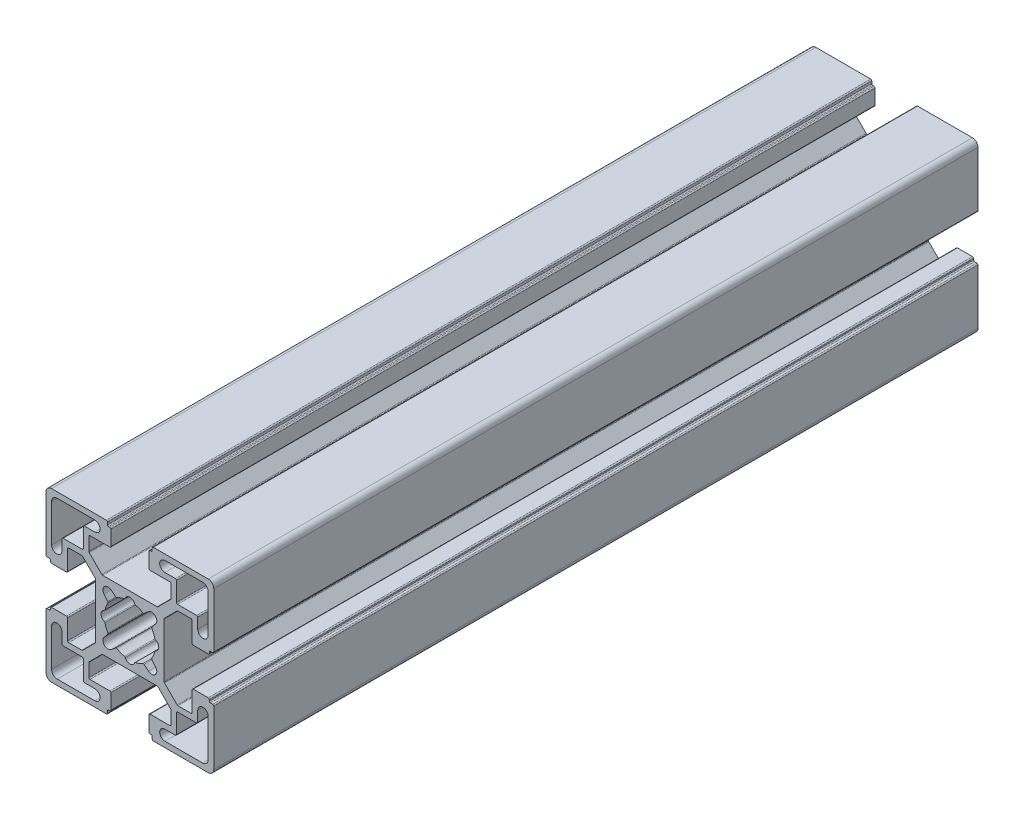
SolidWorks part; units mm, degrees
material "6063-T5"
ref_plane "Plane1" through (0, 0, 0) normal (0, 0, 1) x (1, 0, 0)
ref_plane "Plane2" through (0, 0, 0) normal (0, 1, 0) x (1, 0, 0)
ref_plane "Plane3" through (0, 0, 0) normal (1, 0, 0) x (0, 0, -1)
sketch "Sketch1" plane through (0, 0, 0) normal (0, 0, 1) x (1, 0, 0)
  line L0 (-3.8182, 5.9298) -> (-5.0112, 6.9114)
  line L1 (-6.9114, 5.0112) -> (-5.9298, 3.8182)
  line L2 (-5.9298, -3.8182) -> (-6.9114, -5.0112)
  line L3 (-5.0112, -6.9114) -> (-3.8182, -5.9298)
  line L4 (3.8182, -5.9298) -> (5.0112, -6.9114)
  line L5 (6.9114, -5.0112) -> (5.9298, -3.8182)
  line L6 (5.9298, 3.8182) -> (6.9114, 5.0112)
  line L7 (5.0112, 6.9114) -> (3.8182, 5.9298)
  line L8 (-19.5, -21) -> (-9.4, -21)
  line L9 (-9.4, -18.2) -> (-12.2, -18.2)
  line L10 (-12.5, -17.9) -> (-12.5, -12.8)
  line L11 (-12.8, -12.5) -> (-17.9, -12.5)
  line L12 (-18.2, -12.2) -> (-18.2, -9.4)
  line L13 (-21, -9.4) -> (-21, -19.5)
  line L14 (17.9, -12.5) -> (12.8, -12.5)
  line L15 (12.5, -12.8) -> (12.5, -17.9)
  line L16 (12.2, -18.2) -> (9.4, -18.2)
  line L17 (9.4, -21) -> (19.5, -21)
  line L18 (21, -19.5) -> (21, -9.4)
  line L19 (18.2, -9.4) -> (18.2, -12.2)
  line L20 (19.5, 21) -> (9.4, 21)
  line L21 (9.4, 18.2) -> (12.2, 18.2)
  line L22 (12.5, 17.9) -> (12.5, 12.8)
  line L23 (12.8, 12.5) -> (17.9, 12.5)
  line L24 (18.2, 12.2) -> (18.2, 9.4)
  line L25 (21, 9.4) -> (21, 19.5)
  line L26 (-18.2, 9.4) -> (-18.2, 12.2)
  line L27 (-17.9, 12.5) -> (-12.8, 12.5)
  line L28 (-12.5, 12.8) -> (-12.5, 17.9)
  line L29 (-12.2, 18.2) -> (-9.4, 18.2)
  line L30 (-9.4, 21) -> (-19.5, 21)
  line L31 (-21, 19.5) -> (-21, 9.4)
  line L32 (22.5, 6.3) -> (22.5, 21)
  line L33 (21.6, 6) -> (22.2, 6)
  line L34 (21.3, 5.4) -> (21.3, 5.7)
  line L36 (16.7, 10.7) -> (16.7, 5.4)
  line L37 (12.892, 11) -> (16.4, 11)
  line L38 (9.2879, 7.5201) -> (12.6799, 10.9121)
  line L39 (9.2, -7.308) -> (9.2, 7.308)
  line L40 (12.6799, -10.9121) -> (9.2879, -7.5201)
  line L41 (16.4, -11) -> (12.892, -11)
  line L42 (16.7, -5.4) -> (16.7, -10.7)
  line L44 (21.3, -5.7) -> (21.3, -5.4)
  line L45 (22.2, -6) -> (21.6, -6)
  line L46 (22.5, -21) -> (22.5, -6.3)
  line L47 (6.3, -22.5) -> (21, -22.5)
  line L48 (6, -21.6) -> (6, -22.2)
  line L49 (5.4, -21.3) -> (5.7, -21.3)
  line L51 (10.7, -16.7) -> (5.4, -16.7)
  line L52 (11, -12.892) -> (11, -16.4)
  line L53 (7.5201, -9.2879) -> (10.9121, -12.6799)
  line L54 (-7.4322, -9.2) -> (7.308, -9.2)
  line L55 (-10.9121, -12.6799) -> (-7.4322, -9.2)
  line L56 (-11, -16.4) -> (-11, -12.892)
  line L57 (-5.4, -16.7) -> (-10.7, -16.7)
  line L59 (-5.7, -21.3) -> (-5.4, -21.3)
  line L60 (-6, -22.2) -> (-6, -21.6)
  line L61 (-21, -22.5) -> (-6.3, -22.5)
  line L62 (-22.5, -6.3) -> (-22.5, -21)
  line L63 (-21.6, -6) -> (-22.2, -6)
  line L64 (-21.3, -5.4) -> (-21.3, -5.7)
  line L66 (-16.7, -10.7) -> (-16.7, -5.4)
  line L67 (-12.892, -11) -> (-16.4, -11)
  line L68 (-9.2879, -7.5201) -> (-12.6799, -10.9121)
  line L69 (-9.2, 7.308) -> (-9.2, -7.308)
  line L70 (-12.6799, 10.9121) -> (-9.2879, 7.5201)
  line L71 (-16.4, 11) -> (-12.892, 11)
  line L72 (-16.7, 5.4) -> (-16.7, 10.7)
  line L74 (-21.3, 5.7) -> (-21.3, 5.4)
  line L75 (-22.2, 6) -> (-21.6, 6)
  line L76 (-22.5, 21) -> (-22.5, 6.3)
  line L77 (-6.3, 22.5) -> (-21, 22.5)
  line L78 (-6, 21.6) -> (-6, 22.2)
  line L79 (-5.4, 21.3) -> (-5.7, 21.3)
  line L81 (-10.7, 16.7) -> (-5.4, 16.7)
  line L82 (-11, 12.892) -> (-11, 16.4)
  line L83 (-7.5201, 9.2879) -> (-10.9121, 12.6799)
  line L84 (7.308, 9.2) -> (-7.308, 9.2)
  line L85 (10.9121, 12.6799) -> (7.5201, 9.2879)
  line L86 (11, 16.4) -> (11, 12.892)
  line L87 (5.4, 16.7) -> (10.7, 16.7)
  line L89 (5.7, 21.3) -> (5.4, 21.3)
  line L90 (6, 22.2) -> (6, 21.6)
  line L91 (21, 22.5) -> (6.3, 22.5)
  line L92 (-5.1, 17) -> (-5.1, 21)
  line L93 (-21, 5.1) -> (-17, 5.1)
  line L94 (-17, -5.1) -> (-21, -5.1)
  line L95 (-5.1, -21) -> (-5.1, -17)
  line L96 (5.1, -17) -> (5.1, -21)
  line L97 (21, -5.1) -> (17, -5.1)
  line L98 (17, 5.1) -> (21, 5.1)
  line L99 (5.1, 21) -> (5.1, 17)
  arc A0 (-1.4794, 6.6883) -> (-1.2635, 6.8756) centre (-1.5442, 6.9813) ccw
  arc A1 (-1.4794, 6.6883) -> (-3.4754, 5.9029) centre (0, 0) ccw
  arc A2 (-3.8182, 5.9298) -> (-3.4754, 5.9029) centre (-3.6276, 6.1614) ccw
  arc A3 (-5.0112, 6.9114) -> (-6.9114, 5.0112) centre (-5.869, 5.869) ccw
  arc A4 (-5.9029, 3.4754) -> (-5.9298, 3.8182) centre (-6.1614, 3.6276) ccw
  arc A5 (-5.9029, 3.4754) -> (-6.6883, 1.4794) centre (0, 0) ccw
  arc A6 (-6.8756, 1.2635) -> (-6.6883, 1.4794) centre (-6.9813, 1.5442) ccw
  arc A7 (-6.8756, 1.2635) -> (-6.8756, -1.2635) centre (-6.4, 0) ccw
  arc A8 (-6.6883, -1.4794) -> (-6.8756, -1.2635) centre (-6.9813, -1.5442) ccw
  arc A9 (-6.6883, -1.4794) -> (-5.9029, -3.4754) centre (0, 0) ccw
  arc A10 (-5.9298, -3.8182) -> (-5.9029, -3.4754) centre (-6.1614, -3.6276) ccw
  arc A11 (-6.9114, -5.0112) -> (-5.0112, -6.9114) centre (-5.869, -5.869) ccw
  arc A12 (-3.4754, -5.9029) -> (-3.8182, -5.9298) centre (-3.6276, -6.1614) ccw
  arc A13 (-3.4754, -5.9029) -> (-1.4794, -6.6883) centre (0, 0) ccw
  arc A14 (-1.2635, -6.8756) -> (-1.4794, -6.6883) centre (-1.5442, -6.9812) ccw
  arc A15 (-1.2635, -6.8756) -> (1.2635, -6.8756) centre (0, -6.4) ccw
  arc A16 (1.4794, -6.6883) -> (1.2635, -6.8756) centre (1.5442, -6.9812) ccw
  arc A17 (1.4794, -6.6883) -> (3.4754, -5.9029) centre (0, 0) ccw
  arc A18 (3.8182, -5.9298) -> (3.4754, -5.9029) centre (3.6276, -6.1614) ccw
  arc A19 (5.0112, -6.9114) -> (6.9114, -5.0112) centre (5.869, -5.869) ccw
  arc A20 (5.9029, -3.4754) -> (5.9298, -3.8182) centre (6.1614, -3.6276) ccw
  arc A21 (5.9029, -3.4754) -> (6.6883, -1.4794) centre (0, 0) ccw
  arc A22 (6.8756, -1.2635) -> (6.6883, -1.4794) centre (6.9812, -1.5442) ccw
  arc A23 (6.8756, -1.2635) -> (6.8756, 1.2635) centre (6.4, 0) ccw
  arc A24 (6.6883, 1.4794) -> (6.8756, 1.2635) centre (6.9812, 1.5442) ccw
  arc A25 (6.6883, 1.4794) -> (5.9029, 3.4754) centre (0, 0) ccw
  arc A26 (5.9298, 3.8182) -> (5.9029, 3.4754) centre (6.1614, 3.6276) ccw
  arc A27 (6.9114, 5.0112) -> (5.0112, 6.9114) centre (5.869, 5.869) ccw
  arc A28 (3.4754, 5.9029) -> (3.8182, 5.9298) centre (3.6276, 6.1614) ccw
  arc A29 (3.4754, 5.9029) -> (1.4794, 6.6883) centre (0, 0) ccw
  arc A30 (1.2635, 6.8756) -> (1.4794, 6.6883) centre (1.5442, 6.9813) ccw
  arc A31 (1.2635, 6.8756) -> (-1.2635, 6.8756) centre (0, 6.4) ccw
  arc A32 (-21, -19.5) -> (-19.5, -21) centre (-19.5, -19.5) ccw
  arc A33 (-9.4, -21) -> (-9.4, -18.2) centre (-9.4, -19.6) ccw
  arc A34 (-12.5, -17.9) -> (-12.2, -18.2) centre (-12.2, -17.9) ccw
  arc A35 (-12.5, -12.8) -> (-12.8, -12.5) centre (-12.8, -12.8) ccw
  arc A36 (-18.2, -12.2) -> (-17.9, -12.5) centre (-17.9, -12.2) ccw
  arc A37 (-18.2, -9.4) -> (-21, -9.4) centre (-19.6, -9.4) ccw
  arc A38 (17.9, -12.5) -> (18.2, -12.2) centre (17.9, -12.2) ccw
  arc A39 (12.8, -12.5) -> (12.5, -12.8) centre (12.8, -12.8) ccw
  arc A40 (12.2, -18.2) -> (12.5, -17.9) centre (12.2, -17.9) ccw
  arc A41 (9.4, -18.2) -> (9.4, -21) centre (9.4, -19.6) ccw
  arc A42 (19.5, -21) -> (21, -19.5) centre (19.5, -19.5) ccw
  arc A43 (21, -9.4) -> (18.2, -9.4) centre (19.6, -9.4) ccw
  arc A44 (21, 19.5) -> (19.5, 21) centre (19.5, 19.5) ccw
  arc A45 (9.4, 21) -> (9.4, 18.2) centre (9.4, 19.6) ccw
  arc A46 (12.5, 17.9) -> (12.2, 18.2) centre (12.2, 17.9) ccw
  arc A47 (12.5, 12.8) -> (12.8, 12.5) centre (12.8, 12.8) ccw
  arc A48 (18.2, 12.2) -> (17.9, 12.5) centre (17.9, 12.2) ccw
  arc A49 (18.2, 9.4) -> (21, 9.4) centre (19.6, 9.4) ccw
  arc A50 (-21, 9.4) -> (-18.2, 9.4) centre (-19.6, 9.4) ccw
  arc A51 (-17.9, 12.5) -> (-18.2, 12.2) centre (-17.9, 12.2) ccw
  arc A52 (-12.8, 12.5) -> (-12.5, 12.8) centre (-12.8, 12.8) ccw
  arc A53 (-12.2, 18.2) -> (-12.5, 17.9) centre (-12.2, 17.9) ccw
  arc A54 (-9.4, 18.2) -> (-9.4, 21) centre (-9.4, 19.6) ccw
  arc A55 (-19.5, 21) -> (-21, 19.5) centre (-19.5, 19.5) ccw
  arc A56 (22.2, 6) -> (22.5, 6.3) centre (22.2, 6.3) ccw
  arc A57 (21.6, 6) -> (21.3, 5.7) centre (21.6, 5.7) ccw
  arc A58 (-17, -5.1) -> (-16.7, -5.4) centre (-17, -5.4) cw
  arc A59 (16.7, 10.7) -> (16.4, 11) centre (16.4, 10.7) ccw
  arc A60 (12.892, 11) -> (12.6799, 10.9121) centre (12.892, 10.7) ccw
  arc A61 (9.2879, 7.5201) -> (9.2, 7.308) centre (9.5, 7.308) ccw
  arc A62 (9.2, -7.308) -> (9.2879, -7.5201) centre (9.5, -7.308) ccw
  arc A63 (12.6799, -10.9121) -> (12.892, -11) centre (12.892, -10.7) ccw
  arc A64 (16.4, -11) -> (16.7, -10.7) centre (16.4, -10.7) ccw
  arc A65 (-17, 5.1) -> (-16.7, 5.4) centre (-17, 5.4) ccw
  arc A66 (21.3, -5.7) -> (21.6, -6) centre (21.6, -5.7) ccw
  arc A67 (22.5, -6.3) -> (22.2, -6) centre (22.2, -6.3) ccw
  arc A68 (21, -22.5) -> (22.5, -21) centre (21, -21) ccw
  arc A69 (6, -22.2) -> (6.3, -22.5) centre (6.3, -22.2) ccw
  arc A70 (6, -21.6) -> (5.7, -21.3) centre (5.7, -21.6) ccw
  arc A71 (-5.1, 17) -> (-5.4, 16.7) centre (-5.4, 17) cw
  arc A72 (10.7, -16.7) -> (11, -16.4) centre (10.7, -16.4) ccw
  arc A73 (11, -12.892) -> (10.9121, -12.6799) centre (10.7, -12.892) ccw
  arc A74 (7.5201, -9.2879) -> (7.308, -9.2) centre (7.308, -9.5) ccw
  arc A75 (-10.9121, -12.6799) -> (-11, -12.892) centre (-10.7, -12.892) ccw
  arc A76 (-11, -16.4) -> (-10.7, -16.7) centre (-10.7, -16.4) ccw
  arc A77 (5.1, 17) -> (5.4, 16.7) centre (5.4, 17) ccw
  arc A78 (-5.7, -21.3) -> (-6, -21.6) centre (-5.7, -21.6) ccw
  arc A79 (-6.3, -22.5) -> (-6, -22.2) centre (-6.3, -22.2) ccw
  arc A80 (-22.5, -21) -> (-21, -22.5) centre (-21, -21) ccw
  arc A81 (-22.2, -6) -> (-22.5, -6.3) centre (-22.2, -6.3) ccw
  arc A82 (-21.6, -6) -> (-21.3, -5.7) centre (-21.6, -5.7) ccw
  arc A83 (16.7, 5.4) -> (17, 5.1) centre (17, 5.4) ccw
  arc A84 (-16.7, -10.7) -> (-16.4, -11) centre (-16.4, -10.7) ccw
  arc A85 (-12.892, -11) -> (-12.6799, -10.9121) centre (-12.892, -10.7) ccw
  arc A86 (-9.2879, -7.5201) -> (-9.2, -7.308) centre (-9.5, -7.308) ccw
  arc A87 (-9.2, 7.308) -> (-9.2879, 7.5201) centre (-9.5, 7.308) ccw
  arc A88 (-12.6799, 10.9121) -> (-12.892, 11) centre (-12.892, 10.7) ccw
  arc A89 (-16.4, 11) -> (-16.7, 10.7) centre (-16.4, 10.7) ccw
  arc A90 (17, -5.1) -> (16.7, -5.4) centre (17, -5.4) ccw
  arc A91 (-21.3, 5.7) -> (-21.6, 6) centre (-21.6, 5.7) ccw
  arc A92 (-22.5, 6.3) -> (-22.2, 6) centre (-22.2, 6.3) ccw
  arc A93 (-21, 22.5) -> (-22.5, 21) centre (-21, 21) ccw
  arc A94 (-6, 22.2) -> (-6.3, 22.5) centre (-6.3, 22.2) ccw
  arc A95 (-6, 21.6) -> (-5.7, 21.3) centre (-5.7, 21.6) ccw
  arc A96 (5.1, -17) -> (5.4, -16.7) centre (5.4, -17) cw
  arc A97 (-10.7, 16.7) -> (-11, 16.4) centre (-10.7, 16.4) ccw
  arc A98 (-11, 12.892) -> (-10.9121, 12.6799) centre (-10.7, 12.892) ccw
  arc A99 (-7.5201, 9.2879) -> (-7.308, 9.2) centre (-7.308, 9.5) ccw
  arc A100 (7.308, 9.2) -> (7.5201, 9.2879) centre (7.308, 9.5) ccw
  arc A101 (10.9121, 12.6799) -> (11, 12.892) centre (10.7, 12.892) ccw
  arc A102 (11, 16.4) -> (10.7, 16.7) centre (10.7, 16.4) ccw
  arc A103 (-5.1, -17) -> (-5.4, -16.7) centre (-5.4, -17) ccw
  arc A104 (5.7, 21.3) -> (6, 21.6) centre (5.7, 21.6) ccw
  arc A105 (6.3, 22.5) -> (6, 22.2) centre (6.3, 22.2) ccw
  arc A106 (22.5, 21) -> (21, 22.5) centre (21, 21) ccw
  arc A107 (-21, 5.1) -> (-21.3, 5.4) centre (-21, 5.4) cw
  arc A108 (-21, -5.1) -> (-21.3, -5.4) centre (-21, -5.4) ccw
  arc A109 (-5.1, -21) -> (-5.4, -21.3) centre (-5.4, -21) cw
  arc A110 (5.1, -21) -> (5.4, -21.3) centre (5.4, -21) ccw
  arc A111 (21, -5.1) -> (21.3, -5.4) centre (21, -5.4) cw
  arc A112 (21, 5.1) -> (21.3, 5.4) centre (21, 5.4) ccw
  arc A113 (5.1, 21) -> (5.4, 21.3) centre (5.4, 21) cw
  arc A114 (-5.1, 21) -> (-5.4, 21.3) centre (-5.4, 21) ccw
  point P299 (0, 22.5)
  point P300 (22.5, 22.5)
  point P301 (-22.5, 22.5)
  point P302 (-22.5, 0)
  point P303 (-22.5, -22.5)
  point P304 (0, -22.5)
  point P305 (22.5, -22.5)
  point P306 (22.5, 0)
  point P308 (0, 0)
extrude "Ressalto-extrusão2" add sketch "Sketch1" along normal blind 205 contours L32 A106 L91 A105 L90 A104 L89 L99 A77 L87 A102 L86 A101 L85 A100 L84 A99 L83 A98 L82 A97 L81 A71 L92 L79 A95 L78 A94 L77 A93 L76 A92 L75 A91 L74 L93 A65 L72 A89 L71 A88 L70 A87 L69 A86 L68 A85 L67 A84 L66 A58
